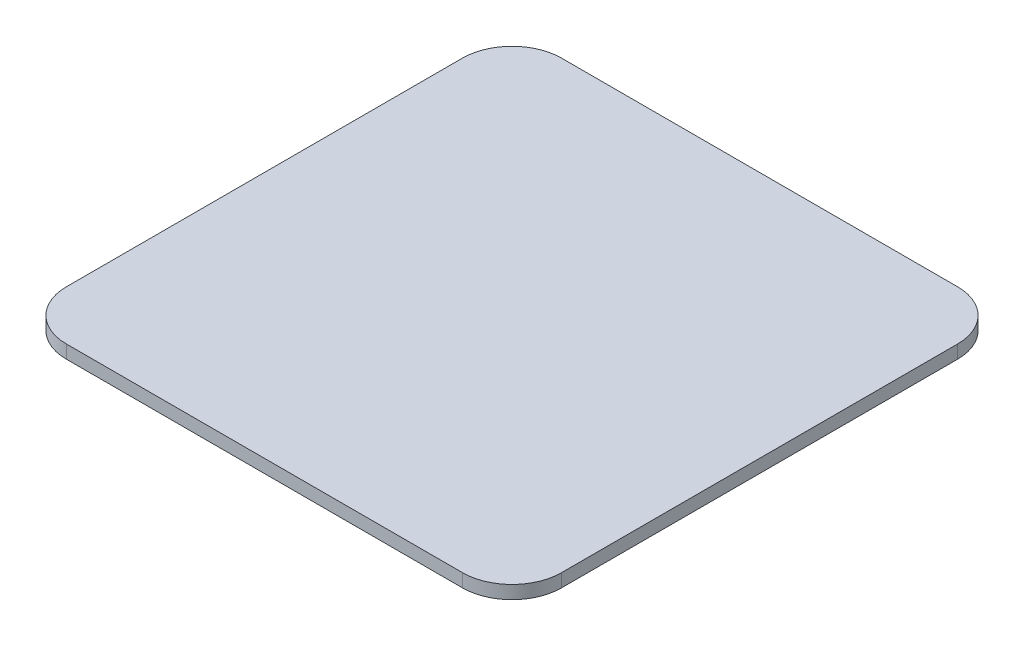
SolidWorks part; units mm, degrees
ref_plane "Front Plane" through (0, 0, 0) normal (0, 0, 1) x (1, 0, 0)
ref_plane "Top Plane" through (0, 0, 0) normal (0, 1, 0) x (1, 0, 0)
ref_plane "Right Plane" through (0, 0, 0) normal (1, 0, 0) x (0, 0, -1)
sketch "Sketch1" plane through (0, 0, 0) normal (0, 1, 0) x (1, 0, 0)
  line L0 (0, 75) -> (0, -75) construction
  line L1 (-75, -75) -> (75, -75)
  line L2 (-75, -75) -> (-75, 75)
  line L3 (-75, 75) -> (75, 75)
  line L4 (75, -75) -> (75, 75)
  line L5 (-75, -75) -> (75, 75) construction
  line L6 (-75, 75) -> (75, -75) construction
  line L7 (-75, 0) -> (75, 0) construction
  line L8 (-75, -60) -> (-60, -60) construction
  line L9 (-60, -60) -> (-60, -75) construction
  arc A2 (-75, -60) -> (-60, -75) centre (-60, -60) ccw
  arc A3 (75, -60) -> (60, -75) centre (60, -60) cw
  arc A4 (-75, 60) -> (-60, 75) centre (-60, 60) cw
  arc A5 (75, 60) -> (60, 75) centre (60, 60) ccw
  point P0 (0, 0)
  point P6 (0, 0)
  dimension "D6" = 15
  dimension "D4" = 15
  dimension "D1" = 150
  dimension "D2" = 150
extrude "Boss-Extrude3" add sketch "Sketch1" along normal blind 4 contours L4 A5 L3 A4 L2 A2 L1 A3
